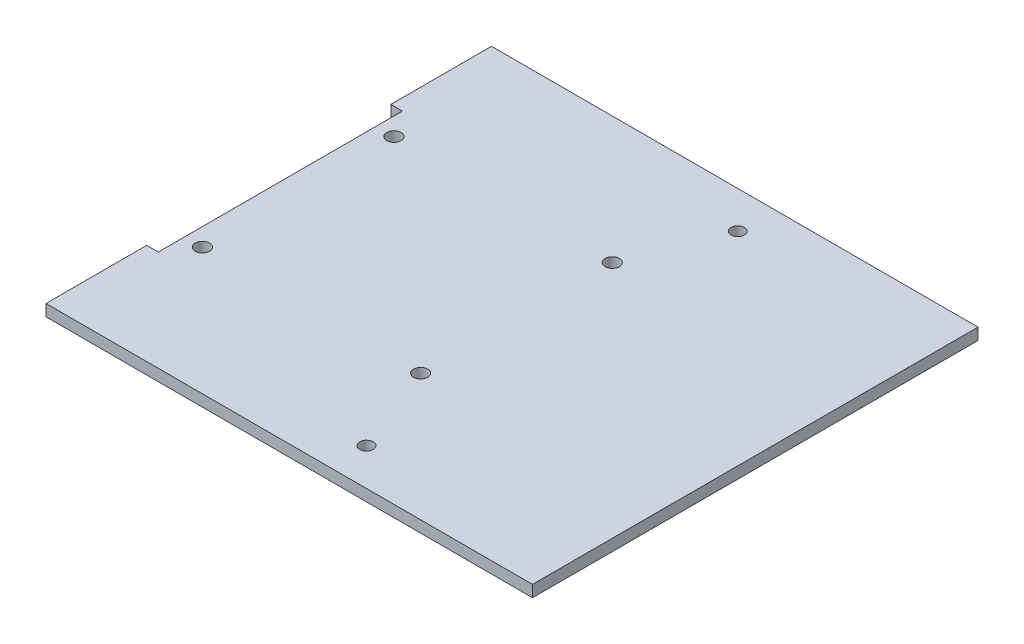
SolidWorks part; units mm, degrees
ref_plane "前视基准面" through (0, 0, 0) normal (0, 0, 1) x (1, 0, 0)
ref_plane "上视基准面" through (0, 0, 0) normal (0, 1, 0) x (1, 0, 0)
ref_plane "右视基准面" through (0, 0, 0) normal (1, 0, 0) x (0, 0, -1)
sketch "草图1" plane through (0, 0, 0) normal (0, 1, 0) x (1, 0, 0)
  line L0 (0, 0) -> (168.1938, 0) construction
  line L1 (0, 0) -> (0, 68.5187) construction
  line L2 (0, 50) -> (-52, 50)
  line L3 (-52, 50) -> (52, 50)
  line L5 (-52, -50) -> (52, -50)
  line L7 (0, 50) -> (52, 50)
  line L8 (52, 50) -> (52, -50)
  line L9 (-52, -50) -> (-52, 50)
  dimension "D1" = 100
  dimension "D3" = 52
  dimension "D4" = 52
extrude "凸台-拉伸1" add sketch "草图1" along normal blind 2.6 contours L9 L5 L8 L3 L2
ref_plane "基准面1" through (-52, 0, 0) normal (-1, 0, 0) x (0, 0, 1)
sketch "草图2" plane through (-52, 0, 0) normal (-1, 0, 0) x (0, 0, 1)
  line L0 (0, 0) -> (60.8879, 0) construction
  line L1 (0, 0) -> (0, 52.5684) construction
  line L4 (-50, 0) -> (50, 0)
  line L5 (-50, 0) -> (-50, 24)
  line L6 (-50, 24) -> (50, 24)
  line L7 (50, 0) -> (50, 24)
  dimension "D1" = 100
  dimension "D2" = 24
extrude "凸台-拉伸2" add sketch "草图2" along normal blind 2.6
ref_plane "基准面2" through (52, 0, 0) normal (1, 0, 0) x (0, 0, -1)
sketch "草图4" plane through (52, 0, 0) normal (1, 0, 0) x (0, 0, -1)
  line L0 (0, 0) -> (83.3328, 0) construction
  line L1 (0, 79.0959) -> (0, 0) construction
  line L3 (-50, 0) -> (50, 0)
  line L4 (-50, 0) -> (-50, 24)
  line L5 (-50, 24) -> (50, 24)
  line L6 (50, 0) -> (50, 24)
  dimension "D1" = 100
  dimension "D2" = 24
extrude "凸台-拉伸3" add sketch "草图4" along normal blind 2.6
ref_plane "基准面3" through (0, 24, 0) normal (0, 1, 0) x (1, 0, 0)
sketch "草图5" plane through (0, 24, 0) normal (0, 1, 0) x (1, 0, 0)
  line L0 (-54.6, 0) -> (-54.6, -62.7888) construction
  line L2 (-54.6, 0) -> (-103.1828, 0) construction
  line L3 (-52, 50) -> (-114, 50)
  line L4 (-52, 50) -> (-52, -50)
  line L5 (-52, -50) -> (-114, -50)
  line L6 (-114, 50) -> (-114, -50)
  dimension "D1" = 62
  dimension "D2" = 100
extrude "凸台-拉伸5" add sketch "草图5" along normal blind 2.6
ref_plane "基准面4" through (0, 24, 0) normal (0, 1, 0) x (1, 0, 0)
sketch "草图7" plane through (0, 24, 0) normal (0, 1, 0) x (1, 0, 0)
  line L0 (54.6, 0) -> (137.447, 0) construction
  line L2 (54.6, 0) -> (54.6, 43.4871) construction
  line L4 (52, -50) -> (114, -50)
  line L5 (52, -50) -> (52, 50)
  line L6 (52, 50) -> (114, 50)
  line L7 (114, -50) -> (114, 50)
  dimension "D1" = 62
  dimension "D2" = 100
extrude "凸台-拉伸6" add sketch "草图7" along normal blind 2.6
sketch "草图8" plane through (0, 24, 0) normal (0, 1, 0) x (1, 0, 0)
  line L13 (-54.6, 50) -> (-114, 50) construction
  line L14 (-114, 30) -> (-54.6, 30)
  line L15 (-114, 30) -> (-114, -30)
  line L16 (-114, -30) -> (-54.6, -30)
  line L17 (-54.6, 30) -> (-54.6, -30)
  line L18 (-114, -50) -> (-54.6, -50) construction
  line L19 (-54.6, -50) -> (-54.6, 50) construction
  line L20 (-114, 50) -> (-114, -50) construction
  dimension "D1" = 20
  dimension "D2" = 20
  dimension "D3" = 0
  dimension "D4" = 0
extrude "切除-拉伸1" cut sketch "草图8" along normal blind 2.6
sketch "草图9" plane through (0, 24, 0) normal (0, -1, 0) x (1, 0, 0)
  line L0 (54.6, 50) -> (114, 50) construction
  line L1 (54.6, 30) -> (114, 30)
  line L2 (54.6, 30) -> (54.6, -30)
  line L3 (54.6, -30) -> (114, -30)
  line L4 (114, 30) -> (114, -30)
  line L5 (114, -50) -> (54.6, -50) construction
  line L6 (54.6, -50) -> (54.6, 50) construction
  line L7 (114, 50) -> (114, -50) construction
  dimension "D1" = 20
  dimension "D2" = 20
  dimension "D3" = 0
  dimension "D4" = 0
extrude "切除-拉伸2" cut sketch "草图9" against normal blind 2.6
ref_plane "基准面6" through (0, 0, 30) normal (0, 0, -1) x (-1, 0, 0)
sketch "草图11" plane through (0, 0, 30) normal (0, 0, -1) x (-1, 0, 0)
  line L2 (-114, 26.6) -> (-54.6, 26.6)
  line L3 (-114, 26.6) -> (-114, 0)
  line L4 (-114, 0) -> (-54.6, 0)
  line L5 (-54.6, 26.6) -> (-54.6, 0)
extrude "凸台-拉伸7" add sketch "草图11" along normal blind 2.6
ref_plane "基准面7" through (0, 0, -30) normal (0, 0, 1) x (1, 0, 0)
sketch "草图12" plane through (0, 0, -30) normal (0, 0, 1) x (1, 0, 0)
  line L2 (54.6, 26.6) -> (114, 26.6)
  line L3 (54.6, 26.6) -> (54.6, 0)
  line L4 (54.6, 0) -> (114, 0)
  line L5 (114, 26.6) -> (114, 0)
extrude "凸台-拉伸8" add sketch "草图12" along normal blind 2.6
ref_plane "基准面8" through (0, 0, -30) normal (0, 0, 1) x (1, 0, 0)
sketch "草图14" plane through (0, 0, -30) normal (0, 0, 1) x (1, 0, 0)
  line L1 (-54.6, 26.6) -> (-114, 26.6)
  line L2 (-54.6, 26.6) -> (-54.6, 0)
  line L3 (-54.6, 0) -> (-114, 0)
  line L4 (-114, 26.6) -> (-114, 0)
extrude "凸台-拉伸9" add sketch "草图14" along normal blind 2.6
ref_plane "基准面9" through (0, 0, 30) normal (0, 0, -1) x (-1, 0, 0)
sketch "草图15" plane through (0, 0, 30) normal (0, 0, -1) x (-1, 0, 0)
  line L2 (54.6, 26.6) -> (114, 26.6)
  line L3 (54.6, 26.6) -> (54.6, 0)
  line L4 (54.6, 0) -> (114, 0)
  line L5 (114, 26.6) -> (114, 0)
extrude "凸台-拉伸10" add sketch "草图15" along normal blind 2.6
sketch "草图16" plane through (0, 2.6, 0) normal (0, 1, 0) x (1, 0, 0)
  line L0 (0, 0) -> (88.5453, 0) construction
  line L1 (0, 0) -> (0, 69.8905) construction
  circle A0 centre (-47.5, 37.465) radius 1.6
  circle A4 centre (47.5, 37.465) radius 1.6
  circle A5 centre (-47.5, -37.465) radius 1.6
  circle A6 centre (47.5, -37.465) radius 1.6
  dimension "D1" = 3.2
  dimension "D2" = 47.5
  dimension "D3" = 37.465
extrude "切除-拉伸3" cut sketch "草图16" against normal through all
sketch "草图17" plane through (0, 2.6, 0) normal (0, 1, 0) x (1, 0, 0)
  line L0 (0, 0) -> (0, -106.8297) construction
  line L1 (-40, 32) -> (40, 32)
  line L2 (-40, 32) -> (-40, -32)
  line L3 (-40, -32) -> (40, -32)
  line L4 (40, 32) -> (40, -32)
  line L5 (0, 0) -> (46.3374, 0) construction
  dimension "D1" = 80
  dimension "D2" = 64
extrude "切除-拉伸4" cut sketch "草图17" against normal through all contours L2 L1 L4 L3
sketch "草图19" plane through (0, 26.6, 0) normal (0, 1, 0) x (1, 0, 0)
sketch "草图21" plane through (0, 0, 0) normal (0, -1, 0) x (1, 0, 0)
  line L1 (-54.6, 27.4) -> (-114, 27.4)
  line L2 (-54.6, 27.4) -> (-54.6, -27.4)
  line L3 (-54.6, -27.4) -> (-114, -27.4)
  line L4 (-114, 27.4) -> (-114, -27.4)
extrude "凸台-拉伸11" add sketch "草图21" against normal blind 2.6
sketch "草图22" plane through (0, 2.6, 0) normal (0, 1, 0) x (1, 0, 0)
  line L0 (-114, -27.4) -> (-114, 27.4) construction
  line L1 (-114, 0) -> (-47.7388, 0) construction
  circle A0 centre (-109, 18) radius 1.6
  circle A1 centre (-109, 0) radius 1.6
  circle A2 centre (-109, -18) radius 1.6
  dimension "D1" = 3.2
  dimension "D3" = 3.2
  dimension "D2" = 5
  dimension "D4" = 18
extrude "切除-拉伸5" cut sketch "草图22" against normal blind 2.6
sketch "草图23" plane through (0, 26.6, 0) normal (0, 1, 0) x (1, 0, 0)
  line L1 (-114, 27.4) -> (-54.6, 27.4)
  line L2 (-114, 27.4) -> (-114, -27.4)
  line L3 (-114, -27.4) -> (-54.6, -27.4)
  line L4 (-54.6, 27.4) -> (-54.6, -27.4)
extrude "凸台-拉伸13" add sketch "草图23" against normal blind 2.6
sketch "草图24" plane through (0, 26.6, 0) normal (0, 1, 0) x (1, 0, 0)
  line L2 (-114, 0) -> (-114, 69.485) construction
  line L3 (-114, 27.4) -> (-104, 27.4)
  line L4 (-114, 27.4) -> (-114, -27.4)
  line L5 (-114, -27.4) -> (-104, -27.4)
  line L6 (-104, 27.4) -> (-104, 0.9702)
  line L7 (-94.7, 6.15) -> (-72, 6.15)
  line L8 (-94.7, 6.15) -> (-94.7, 0.9702)
  line L9 (-94.7, -6.15) -> (-72, -6.15)
  line L10 (-72, 6.15) -> (-72, 0.9702)
  line L11 (-52, -50) -> (-52, 50) construction
  line L12 (-104, -1.0298) -> (-104, -27.4)
  line L13 (-104, 0.9702) -> (-94.7, 0.9702)
  line L15 (-104, -1.0298) -> (-94.7, -1.0298)
  line L17 (-72, 0.9702) -> (-62.7, 0.9702)
  line L19 (-72, -1.0298) -> (-62.7, -1.0298)
  line L20 (-62.7, 0.9702) -> (-62.7, -1.0298)
  line L21 (-94.7, -1.0298) -> (-94.7, -6.15)
  line L22 (-72, -1.0298) -> (-72, -6.15)
  line L23 (-62.7, 0) -> (11.6044, 0) construction
  dimension "D1" = 54.8
  dimension "D2" = 0
  dimension "D4" = 22.7
  dimension "D5" = 12.3
  dimension "D6" = 20
  dimension "D7" = 2
  dimension "D8" = 9.3
  dimension "D9" = 9.3
extrude "切除-拉伸8" cut sketch "草图24" against normal blind 2.6 contours L7 L10 L17 L20 L19 L22 L9 L21 L15 L12 L5 L4 L3 L6 L13 L8
sketch "草图25" plane through (-54.6, 0, 0) normal (-1, 0, 0) x (0, 0, 1)
  line L2 (-27.4, 24) -> (27.4, 24)
  line L3 (-27.4, 24) -> (-27.4, 2.6)
  line L4 (-27.4, 2.6) -> (27.4, 2.6)
  line L5 (27.4, 24) -> (27.4, 2.6)
extrude "切除-拉伸9" cut sketch "草图25" against normal blind 2.6
sketch "草图28" plane through (0, 0, 30) normal (0, 0, 1) x (1, 0, 0)
  line L0 (-54.6, 24) -> (-54.6, 0) construction
  line L1 (-54.6, 12) -> (-123.8904, 12) construction
  circle A0 centre (-87.2, 20.75) radius 1.5
  circle A1 centre (-87.2, 3.25) radius 1.5
  dimension "D1" = 3
  dimension "D2" = 32.6
  dimension "D3" = 17.5
extrude "切除-拉伸11" cut sketch "草图28" against normal up to surface and the other way through all up to face at (-84.3, 12, -30)
sketch "草图31" plane through (0, 2.6, 0) normal (0, 1, 0) x (1, 0, 0)
  line L0 (-88.5519, -27.4) -> (-114, -27.4) construction
  line L1 (-52, 27.4) -> (-93.9958, 27.4)
  line L2 (-52, 27.4) -> (-52, -27.4)
  line L3 (-52, -27.4) -> (-93.9958, -27.4)
  line L4 (-93.9958, 27.4) -> (-93.9958, -27.4)
extrude "切除-拉伸14" cut sketch "草图31" against normal blind 2.6
sketch "草图32" plane through (0, 0, 30) normal (0, 0, 1) x (1, 0, 0)
  line L1 (54.6, 24) -> (114, 24)
  line L2 (54.6, 24) -> (54.6, 0)
  line L3 (54.6, 0) -> (114, 0)
  line L4 (114, 24) -> (114, 0)
extrude "切除-拉伸15" cut sketch "草图32" against normal blind 70.6
sketch "草图33" plane through (0, 2.6, 0) normal (0, 1, 0) x (1, 0, 0)
  line L1 (-52, 50) -> (52, 50)
  line L2 (-52, 50) -> (-52, -50)
  line L3 (-52, -50) -> (52, -50)
  line L4 (52, 50) -> (52, -50)
extrude "切除-拉伸16" cut sketch "草图33" against normal blind 2.6
sketch "草图34" plane through (0, 0, 0) normal (0, -1, 0) x (1, 0, 0)
  line L0 (52, 50) -> (52, -50) construction
  line L1 (-52, 50) -> (52, 50)
  line L2 (-52, 50) -> (-52, -49.6726)
  line L3 (-52, -49.6726) -> (52, -49.6726)
  line L4 (52, 50) -> (52, -49.6726)
extrude "凸台-拉伸14" add sketch "草图34" against normal blind 2.6
sketch "草图35" plane through (0, 2.6, 0) normal (0, 1, 0) x (1, 0, 0)
  line L0 (0, 0) -> (174.9155, 0) construction
  line L1 (0, 0) -> (0, 73.4475) construction
  line L4 (-42, 24) -> (12, 24) construction
  line L5 (-42, 24) -> (-42, -24) construction
  line L6 (-42, -24) -> (12, -24) construction
  line L7 (12, 24) -> (12, -24) construction
  line L8 (-52, 27.4) -> (-52, 49.6726) construction
  circle A0 centre (-39.5, 21.5) radius 1.6
  circle A2 centre (9.5, 21.5) radius 1.6
  circle A3 centre (9.5, -21.5) radius 1.6
  circle A4 centre (-39.5, -21.5) radius 1.6
  dimension "D4" = 3.2
  dimension "D5" = 2.5
  dimension "D6" = 2.5
  dimension "D7" = 3.2
  dimension "D8" = 2.5
  dimension "D9" = 2.5
  dimension "D1" = 54
  dimension "D2" = 48
  dimension "D3" = 10
extrude "切除-拉伸24" cut sketch "草图35" against normal blind 2.6
sketch "草图36" plane through (0, 26.6, 0) normal (0, 1, 0) x (1, 0, 0)
  line L0 (52, -50) -> (114, -50) construction
  line L1 (114, 50) -> (54.6, 50)
  line L2 (114, 50) -> (114, -50)
  line L3 (114, -50) -> (54.6, -50)
  line L4 (54.6, 50) -> (54.6, -50)
extrude "切除-拉伸25" cut sketch "草图36" against normal blind 2.6
sketch "草图37" plane through (54.6, 0, 0) normal (1, 0, 0) x (0, 0, -1)
  line L0 (0, 0) -> (0, 48.9545) construction
  line L1 (-50, 0) -> (50, 0) construction
  line L2 (50, 13.3) -> (-60.8276, 13.3) construction
  line L4 (-18, 14.6) -> (18, 14.6)
  line L5 (-18, 14.6) -> (-18, 12)
  line L6 (-18, 12) -> (18, 12)
  line L7 (18, 14.6) -> (18, 12)
  dimension "D1" = 2.6
  dimension "D2" = 36
  dimension "D3" = 12
extrude "凸台-拉伸17" add sketch "草图37" along normal blind 36
sketch "草图41" plane through (54.6, 0, 0) normal (1, 0, 0) x (0, 0, -1)
  line L0 (-50, 26.6) -> (50, 26.6) construction
  line L1 (-18, 14.6) -> (18, 14.6)
  line L2 (-18, 14.6) -> (-18, 26.6)
  line L3 (-18, 26.6) -> (18, 26.6)
  line L4 (18, 14.6) -> (18, 26.6)
  dimension "D1" = 36
extrude "切除-拉伸27" cut sketch "草图41" against normal blind 2.6
sketch "草图42" plane through (0, 14.6, 0) normal (0, 1, 0) x (1, 0, 0)
  line L0 (90.6, 18) -> (54.6, 18) construction
  line L4 (90.6, 18) -> (90.6, -18) construction
  line L5 (90.6, 0) -> (52, 0) construction
  circle A0 centre (88.1, 15.5) radius 1.6
  circle A1 centre (88.1, -15.5) radius 1.6
  circle A2 centre (57.1, 15.5) radius 1.6
  circle A3 centre (57.1, -15.5) radius 1.6
  dimension "D1" = 3.2
  dimension "D2" = 2.5
  dimension "D3" = 2.5
  dimension "D4" = 2
extrude "切除-拉伸28" cut sketch "草图42" against normal blind 2.6
sketch "草图43" plane through (0, 14.6, 0) normal (0, 1, 0) x (1, 0, 0)
  line L0 (90.6, 0) -> (48.4873, 0) construction
  line L1 (90.6, 18) -> (90.6, -18) construction
  line L2 (57.1, 15.5) -> (88.1, 15.5)
  line L3 (72.6, 15.5) -> (72.6, -18) construction
  line L4 (90.6, -18) -> (54.6, -18) construction
  circle A0 centre (61.1, 14.5) radius 2
  circle A1 centre (84.1, 14.5) radius 2
  circle A2 centre (84.1, -14.5) radius 2
  circle A3 centre (61.1, -14.5) radius 2
  dimension "D1" = 4
  dimension "D3" = 11.5
  dimension "D4" = 14.5
extrude "切除-拉伸29" cut sketch "草图43" against normal blind 2.6 contours A0 | A1 | A3 | A2
sketch "草图44" plane through (0, 26.6, 0) normal (0, 1, 0) x (1, 0, 0)
  line L1 (-52, 49.6726) -> (52, 49.6726)
  line L2 (-52, 49.6726) -> (-52, -50)
  line L3 (-52, -50) -> (52, -50)
  line L4 (52, 49.6726) -> (52, -50)
extrude "凸台-拉伸18" add sketch "草图44" against normal blind 2.6
sketch "草图45" plane through (0, 26.6, 0) normal (0, 1, 0) x (1, 0, 0)
  line L0 (-61.404, 0) -> (112.1459, 0) construction
  line L1 (-50, 40) -> (50, 40) construction
  line L2 (-50, 40) -> (-50, -40) construction
  line L3 (-50, -40) -> (50, -40) construction
  line L4 (50, 40) -> (50, -40) construction
  line L5 (0, 0) -> (0, 74.2403) construction
  circle A0 centre (-47.5, -37.465) radius 1.6
  circle A1 centre (-47.5, 37.465) radius 1.6
  circle A2 centre (47.5, -37.465) radius 1.6
  circle A3 centre (47.5, 37.465) radius 1.6
  dimension "D1" = 3.2
  dimension "D2" = 2.535
  dimension "D3" = 2.5
extrude "切除-拉伸30" cut sketch "草图45" against normal blind 2.6
sketch "草图46" plane through (0, 26.6, 0) normal (0, 1, 0) x (1, 0, 0)
  line L0 (0, 0) -> (106.198, 0) construction
  line L1 (-40, 32) -> (40, 32)
  line L2 (-40, 32) -> (-40, -32)
  line L3 (-40, -32) -> (40, -32)
  line L4 (40, 32) -> (40, -32)
  line L5 (0, 0) -> (0, 58.9714) construction
  dimension "D1" = 80
  dimension "D2" = 64
extrude "切除-拉伸31" cut sketch "草图46" against normal blind 2.6 contours L2 L1 L4 L3
sketch "草图47" plane through (0, 2.6, 0) normal (0, 1, 0) x (1, 0, 0)
  line L0 (-40, 0) -> (22.2042, 0) construction
  line L3 (-15, 21.5) -> (-15, -18.6922) construction
  line L4 (-35, 15) -> (5, 15)
  line L5 (-35, 15) -> (-35, -15)
  line L6 (-35, -15) -> (5, -15)
  line L7 (5, 15) -> (5, -15)
  dimension "D1" = 40
  dimension "D2" = 30
extrude "切除-拉伸32" cut sketch "草图47" against normal blind 2.6 contours L5 L4 L7 L6
sketch "草图48" plane through (0, 26.6, 0) normal (0, 1, 0) x (1, 0, 0)
  line L1 (-40, 32) -> (-52, 32)
  line L2 (-40, 32) -> (-40, -32)
  line L3 (-40, -32) -> (-52, -32)
  line L4 (-52, 32) -> (-52, -32)
  dimension "D1" = 12
extrude "切除-拉伸33" cut sketch "草图48" against normal blind 2.6
sketch "草图49" plane through (0, 2.6, 0) normal (0, 1, 0) x (1, 0, 0)
  line L6 (-35, 15) -> (5, 15)
  line L7 (-35, 15) -> (-35, 35.5471)
  line L8 (-35, 35.5471) -> (5, 35.5471)
  line L9 (5, 15) -> (5, 35.5471)
  line L10 (-35, -15) -> (5, -15)
  line L11 (-35, -15) -> (-35, -35)
  line L12 (-35, -35) -> (5, -35)
  line L13 (5, -15) -> (5, -35)
  dimension "D1" = 20
extrude "切除-拉伸34" cut sketch "草图49" against normal blind 2.6 contours L11 L10 L13 L12
sketch "草图50" plane through (0, 2.6, 0) normal (0, 1, 0) x (1, 0, 0)
  line L1 (-35, 15) -> (4.9378, 15)
  line L2 (-35, 15) -> (-35, 35)
  line L3 (-35, 35) -> (4.9378, 35)
  line L4 (4.9378, 15) -> (4.9378, 35)
  dimension "D1" = 20
extrude "切除-拉伸35" cut sketch "草图50" against normal blind 2.6
sketch "草图51" plane through (0, 14.6, 0) normal (0, 1, 0) x (1, 0, 0)
  line L4 (52, 18) -> (90.6, -18) construction
  line L6 (90.6, 18) -> (52, -18) construction
  circle A1 centre (71.3, 0) radius 9
  dimension "D1" = 18
extrude "切除-拉伸36" cut sketch "草图51" against normal blind 2.6
sketch "草图52" plane through (0, 0, 30) normal (0, 0, 1) x (1, 0, 0)
  line L0 (-87.2, 20.75) -> (-87.2, 3.25) construction
  line L1 (-87.2, 12) -> (-58.053, 12) construction
  line L2 (-67.2, 4.5) -> (-82.2, 4.5)
  line L3 (-107.2, 19.5) -> (-92.2, 19.5)
  line L4 (-107.2, 19.5) -> (-107.2, 4.5)
  line L5 (-107.2, 4.5) -> (-92.2, 4.5)
  line L6 (-92.2, 19.5) -> (-92.2, 4.5)
  line L7 (-82.2, 19.5) -> (-82.2, 4.5)
  line L8 (-67.2, 19.5) -> (-82.2, 19.5)
  line L9 (-67.2, 19.5) -> (-67.2, 4.5)
  dimension "D1" = 15
  dimension "D2" = 15
  dimension "D3" = 5
extrude "切除-拉伸38" cut sketch "草图52" against normal up to surface (60 mm away) up to face at (-88.7, 20.75, -30)
sketch "草图55" plane through (52, 0, 0) normal (1, 0, 0) x (0, 0, -1)
  line L1 (-18, 26.6) -> (18, 26.6)
  line L2 (-18, 26.6) -> (-18, 24)
  line L3 (-18, 24) -> (18, 24)
  line L4 (18, 26.6) -> (18, 24)
extrude "切除-拉伸39" cut sketch "草图55" against normal up to surface (12 mm away) up to face at (40, 25.3, 0)
sketch "草图56" plane through (54.6, 0, 0) normal (1, 0, 0) x (0, 0, -1)
  line L0 (-50, 13.3) -> (50, 13.3) construction
  line L3 (0, 0) -> (0, 44.005) construction
  line L5 (-50, 26.6) -> (-50, 0) construction
  line L6 (-42, 18.3) -> (-32, 18.3)
  line L7 (-42, 18.3) -> (-42, 8.3)
  line L8 (-42, 8.3) -> (-32, 8.3)
  line L9 (-32, 18.3) -> (-32, 8.3)
  line L10 (42, 8.3) -> (32, 8.3)
  line L11 (32, 18.3) -> (32, 8.3)
  line L12 (42, 18.3) -> (32, 18.3)
  line L13 (42, 18.3) -> (42, 8.3)
  dimension "D1" = 10
  dimension "D2" = 10
  dimension "D3" = 8
extrude "切除-拉伸40" cut sketch "草图56" against normal up to surface (109.2 mm away)
sketch "草图57" plane through (0, 0, 0) normal (0, -1, 0) x (1, 0, 0)
  line L0 (0, 0) -> (134.0882, 0) construction
  line L1 (0, 0) -> (0, 78.3548) construction
  line L2 (-52, -49.6726) -> (52, -49.6726) construction
  circle A0 centre (9, -41.6726) radius 1.5
  circle A1 centre (9, 41.6726) radius 1.5
  dimension "D1" = 3
  dimension "D3" = 9
  dimension "D2" = 8
extrude "切除-拉伸41" cut sketch "草图57" against normal up to surface (26.6 mm away) up to face at (-47.5, 26.6, -39.065)
sketch "草图58" plane through (0, 0, -49.6726) normal (0, 0, -1) x (-1, 0, 0)
  line L0 (-52, 24) -> (-52, 26.6) construction
  line L1 (52, 2.6) -> (-52, 2.6)
  line L2 (52, 2.6) -> (52, 0)
  line L3 (52, 0) -> (-52, 0)
  line L4 (-52, 2.6) -> (-52, 0)
  line L5 (-52, 26.6) -> (52, 26.6)
  line L6 (-52, 26.6) -> (-52, 24)
  line L7 (-52, 24) -> (52, 24)
  line L8 (52, 26.6) -> (52, 24)
extrude "凸台-拉伸19" add sketch "草图58" along normal up to surface (0.3274 mm away) contours L8 L5 L6 L7 | L2 L1 L4 L3 up to face at (-73.5333, 16.8667, -50)
sketch "草图59" plane through (0, 0, -30) normal (0, 0, -1) x (-1, 0, 0)
  line L1 (54.6, 0) -> (114, 0)
  line L2 (54.6, 0) -> (54.6, 24)
  line L3 (54.6, 24) -> (114, 24)
  line L4 (114, 0) -> (114, 24)
extrude "切除-拉伸42" cut sketch "草图59" against normal up to surface (60 mm away) up to face at (-99.7, 12, 30)
sketch "草图60" plane through (0, 26.6, 0) normal (0, 1, 0) x (1, 0, 0)
  line L1 (-114, 50) -> (54.6, 50)
  line L2 (-114, 50) -> (-114, -50)
  line L3 (-114, -50) -> (54.6, -50)
  line L4 (54.6, 50) -> (54.6, -50)
extrude "切除-拉伸43" cut sketch "草图60" against normal blind 2.6
sketch "草图61" plane through (-52, 0, 0) normal (1, 0, 0) x (0, 0, -1)
  line L1 (-50, 24) -> (50, 24)
  line L2 (-50, 24) -> (-50, 2.6)
  line L3 (-50, 2.6) -> (50, 2.6)
  line L4 (50, 24) -> (50, 2.6)
extrude "切除-拉伸44" cut sketch "草图61" against normal blind 200 and the other way blind 200
sketch "草图62" plane through (4.9378, 0, 0) normal (-1, 0, 0) x (0, 0, 1)
  line L1 (-35, 2.6) -> (-15, 2.6)
  line L2 (-35, 2.6) -> (-35, 0)
  line L3 (-35, 0) -> (-15, 0)
  line L4 (-15, 2.6) -> (-15, 0)
extrude "凸台-拉伸20" add sketch "草图62" along normal up to surface (39.9378 mm away) up to face at (-35, 1.3, 0)
sketch "草图63" plane through (0, 0, -15) normal (0, 0, 1) x (1, 0, 0)
  line L1 (-35, 2.6) -> (5, 2.6)
  line L2 (-35, 2.6) -> (-35, 0)
  line L3 (-35, 0) -> (5, 0)
  line L4 (5, 2.6) -> (5, 0)
extrude "凸台-拉伸21" add sketch "草图63" along normal up to surface (50 mm away) up to face at (-15, 1.3, 35)
sketch "草图64" plane through (0, 0, 0) normal (0, -1, 0) x (1, 0, 0)
  line L0 (-39.5, 21.5) -> (-39.5, -26.4064) construction
  line L1 (9.5, -21.5) -> (9.5, 28.2288) construction
  line L2 (0, 0) -> (-63.9974, 0) construction
  line L3 (-52, 27.4) -> (-52, -27.4) construction
  circle A0 centre (-48, 21.5) radius 1.6
  circle A1 centre (-48, -21.5) radius 1.6
  circle A2 centre (1, 21.5) radius 1.6
  circle A3 centre (1, -21.5) radius 1.6
  point P17 (0, 21.5)
  point P18 (-12.9903, -21.5)
  point P19 (-46.4508, -21.5)
  dimension "D1" = 3.2
  dimension "D2" = 4
  dimension "D3" = 49
  dimension "D4" = 49
extrude "切除-拉伸45" cut sketch "草图64" against normal blind 2.6
sketch "草图65" plane through (0, 0, 0) normal (0, -1, 0) x (1, 0, 0)
  circle A0 centre (-39.5, 21.5) radius 1.6
  circle A1 centre (-39.5, -21.5) radius 1.6
  circle A2 centre (9.5, -21.5) radius 1.6
  circle A3 centre (9.5, 21.5) radius 1.6
extrude "凸台-拉伸23" add sketch "草图65" against normal blind 2.6
